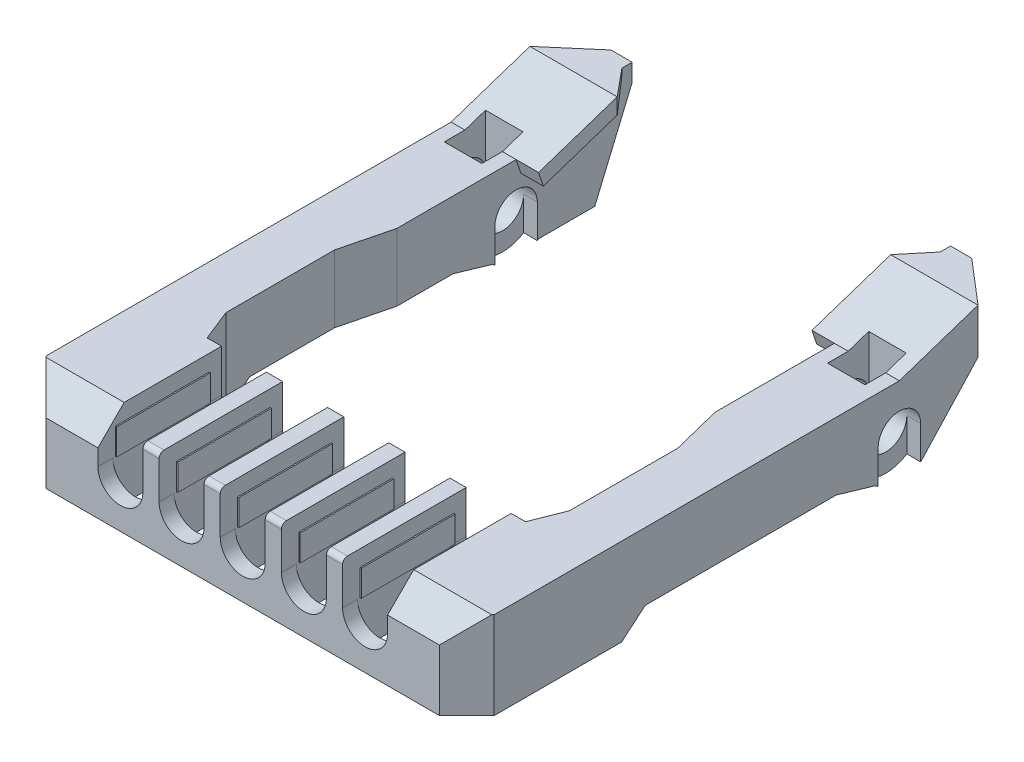
SolidWorks part; units mm, degrees
material "ABS"
ref_plane "Front Plane" through (0, 0, 0) normal (0, 0, 1) x (1, 0, 0)
ref_plane "Top Plane" through (0, 0, 0) normal (0, 1, 0) x (1, 0, 0)
ref_plane "Right Plane" through (0, 0, 0) normal (1, 0, 0) x (0, 0, -1)
sketch "Sketch1" plane through (0, 0, 0) normal (0, 1, 0) x (1, 0, 0)
  line L1 (-17.95, -4.95) -> (17.95, -4.95)
  line L2 (-17.95, -4.95) -> (-17.95, 4.95)
  line L3 (-17.95, 4.95) -> (17.95, 4.95)
  line L4 (17.95, -4.95) -> (17.95, 4.95)
  line L5 (-17.95, -4.95) -> (17.95, 4.95) construction
  line L6 (-17.95, 4.95) -> (17.95, -4.95) construction
  point P0 (0, 0)
extrude "Boss-Extrude1" add sketch "Sketch1" along normal blind 7 contours L2 L1 L4 L3
chamfer "Chamfer1" distance 2.192 angle 45 2 edges at (-17.95, 3.5, 4.95) (17.95, 3.5, 4.95)
sketch "Sketch2" plane through (0, 7, 0) normal (0, 1, 0) x (1, 0, 0)
  line L0 (-17.95, 4.95) -> (17.95, 4.95) construction
  line L1 (11.6, 4.95) -> (8, 4.95)
  line L2 (11.6, 4.95) -> (11.6, -4.95)
  line L3 (11.6, -4.95) -> (8, -4.95)
  line L4 (8, 4.95) -> (8, -4.95)
  line L5 (-15.758, -4.95) -> (15.758, -4.95) construction
  line L7 (6.7, 4.95) -> (6.7, -4.95)
  line L8 (6.7, 4.95) -> (3.1, 4.95)
  line L9 (3.1, 4.95) -> (3.1, -4.95)
  line L10 (6.7, -4.95) -> (3.1, -4.95)
  line L11 (1.8, 4.95) -> (1.8, -4.95)
  line L12 (1.8, 4.95) -> (-1.8, 4.95)
  line L13 (-1.8, 4.95) -> (-1.8, -4.95)
  line L14 (1.8, -4.95) -> (-1.8, -4.95)
  line L15 (-3.1, 4.95) -> (-3.1, -4.95)
  line L16 (-3.1, 4.95) -> (-6.7, 4.95)
  line L17 (-6.7, 4.95) -> (-6.7, -4.95)
  line L18 (-3.1, -4.95) -> (-6.7, -4.95)
  line L19 (-8, 4.95) -> (-8, -4.95)
  line L20 (-8, 4.95) -> (-11.6, 4.95)
  line L21 (-11.6, 4.95) -> (-11.6, -4.95)
  line L22 (-8, -4.95) -> (-11.6, -4.95)
  line L23 (17.95, -2.758) -> (17.95, 4.95) construction
  dimension "D2" = 3.6
  dimension "D3" = 5
  dimension "D4" = 3.6
  dimension "D5" = 1.3
  dimension "D6" = 3.6
  dimension "D7" = 1.3
  dimension "D8" = 3.6
  dimension "D9" = 1.3
  dimension "D10" = 3.6
  dimension "D11" = 1.3
  dimension "D12" = 16.15
extrude "Cut-Extrude1" cut sketch "Sketch2" against normal blind 3.4
chamfer "Chamfer2" distance 2.1 angle 45 2 edges at (13.679, 7, 4.95) (-13.679, 7, 4.95)
fillet "Fillet1" radius 0.4 4 edges at (7.35, 7, 4.95) (2.45, 7, 4.95) (-2.45, 7, 4.95) (-7.35, 7, 4.95)
sketch "Sketch3" plane through (0, 0, 4.95) normal (0, 0, 1) x (1, 0, 0)
  line L0 (17.95, 7) -> (17.95, 0) construction
  line L4 (-15.758, 0) -> (15.758, 0) construction
  circle A0 centre (9.8, 3.6) radius 1.8
  circle A1 centre (4.9, 3.6) radius 1.8
  circle A2 centre (0, 3.6) radius 1.8
  circle A3 centre (-4.9, 3.6) radius 1.8
  circle A4 centre (-9.8, 3.6) radius 1.8
  dimension "D1" = 3.6
  dimension "D2" = 3.6
  dimension "D6" = 4.9
  dimension "D7" = 4.9
  dimension "D3" = 5
  dimension "D4" = 4.9
  dimension "D5" = 4.9
  dimension "D8" = 17.95
extrude "Cut-Extrude2" cut sketch "Sketch3" against normal through all
sketch "Sketch4" plane through (-6.7, 0, 0) normal (1, 0, 0) x (0, 0, -1)
  line L0 (-2.758, 7) -> (4.95, 7) construction
  line L1 (3.95, 5.7) -> (-3.55, 5.7)
  line L2 (3.95, 5.7) -> (3.95, 3.6)
  line L3 (3.95, 3.6) -> (-3.55, 3.6)
  line L4 (-3.55, 5.7) -> (-3.55, 3.6)
  line L5 (-4.95, 0) -> (-4.95, 4.9) construction
  dimension "D1" = 1.3
  dimension "D2" = 7.5
  dimension "D3" = 3.4
  dimension "D4" = 1.4
extrude "Boss-Extrude2" add sketch "Sketch4" along normal blind 0.1 contours L2 L1 L4 L3
sketch "Sketch5" plane through (-1.8, 0, 0) normal (1, 0, 0) x (0, 0, -1)
  line L0 (3.95, 5.7) -> (-3.55, 5.7)
  line L1 (3.95, 5.7) -> (3.95, 3.6)
  line L2 (3.95, 3.6) -> (-3.55, 3.6)
  line L3 (-3.55, 5.7) -> (-3.55, 3.6)
  line L4 (-2.758, 7) -> (4.95, 7) construction
  line L5 (-4.95, 0) -> (-4.95, 4.9) construction
  dimension "D1" = 1.3
  dimension "D2" = 1.4
extrude "Boss-Extrude3" add sketch "Sketch5" along normal blind 0.1
sketch "Sketch6" plane through (3.1, 0, 0) normal (1, 0, 0) x (0, 0, -1)
  line L0 (3.95, 5.7) -> (-3.55, 5.7)
  line L1 (3.95, 5.7) -> (3.95, 3.6)
  line L2 (3.95, 3.6) -> (-3.55, 3.6)
  line L3 (-3.55, 5.7) -> (-3.55, 3.6)
  line L4 (-2.758, 7) -> (4.95, 7) construction
  line L5 (-4.95, 0) -> (-4.95, 4.9) construction
  dimension "D1" = 1.3
  dimension "D2" = 1.4
  dimension "D3" = 7.5
extrude "Boss-Extrude4" add sketch "Sketch6" along normal blind 0.1
sketch "Sketch7" plane through (8, 0, 0) normal (1, 0, 0) x (0, 0, -1)
  line L0 (3.95, 5.7) -> (-3.55, 5.7)
  line L1 (3.95, 5.7) -> (3.95, 3.6)
  line L2 (3.95, 3.6) -> (-3.55, 3.6)
  line L3 (-3.55, 5.7) -> (-3.55, 3.6)
  line L4 (-2.758, 7) -> (4.95, 7) construction
  line L5 (-4.95, 0) -> (-4.95, 4.9) construction
  dimension "D1" = 1.3
  dimension "D2" = 1.4
  dimension "D3" = 7.5
extrude "Boss-Extrude5" add sketch "Sketch7" along normal blind 0.1
sketch "Sketch8" plane through (-11.6, 0, 0) normal (1, 0, 0) x (0, 0, -1)
  line L0 (3.95, 5.7) -> (-3.55, 5.7)
  line L1 (3.95, 5.7) -> (3.95, 3.6)
  line L2 (3.95, 3.6) -> (-3.55, 3.6)
  line L3 (-3.55, 5.7) -> (-3.55, 3.6)
  line L4 (-2.758, 7) -> (4.95, 7) construction
  line L5 (-4.95, 0) -> (-4.95, 4.9) construction
  dimension "D1" = 1.3
  dimension "D2" = 1.4
extrude "Boss-Extrude6" add sketch "Sketch8" along normal blind 0.1
sketch "Sketch9" plane through (-8, 0, 0) normal (-1, 0, 0) x (0, 0, 1)
  line L0 (3.55, 5.7) -> (-3.95, 5.7)
  line L1 (3.55, 5.7) -> (3.55, 3.6)
  line L2 (3.55, 3.6) -> (-3.95, 3.6)
  line L3 (-3.95, 5.7) -> (-3.95, 3.6)
  line L4 (2.758, 7) -> (-4.95, 7) construction
  line L5 (4.95, 4.9) -> (4.95, 0) construction
  dimension "D1" = 1.3
  dimension "D2" = 1.4
  dimension "D3" = 7.5
extrude "Boss-Extrude7" add sketch "Sketch9" along normal blind 0.1
sketch "Sketch10" plane through (-3.1, 0, 0) normal (-1, 0, 0) x (0, 0, 1)
  line L0 (3.55, 5.7) -> (-3.95, 5.7)
  line L1 (3.55, 5.7) -> (3.55, 3.6)
  line L2 (3.55, 3.6) -> (-3.95, 3.6)
  line L3 (-3.95, 5.7) -> (-3.95, 3.6)
  line L4 (2.758, 7) -> (-4.95, 7) construction
  line L5 (4.95, 4.9) -> (4.95, 0) construction
  dimension "D1" = 1.3
  dimension "D2" = 1.4
  dimension "D3" = 7.5
extrude "Boss-Extrude8" add sketch "Sketch10" along normal blind 0.1
sketch "Sketch11" plane through (1.8, 0, 0) normal (-1, 0, 0) x (0, 0, 1)
  line L0 (3.55, 5.7) -> (-3.95, 5.7)
  line L1 (3.55, 5.7) -> (3.55, 3.6)
  line L2 (3.55, 3.6) -> (-3.95, 3.6)
  line L3 (-3.95, 5.7) -> (-3.95, 3.6)
  line L4 (2.758, 7) -> (-4.95, 7) construction
  line L5 (4.95, 4.9) -> (4.95, 0) construction
  dimension "D1" = 1.3
  dimension "D2" = 1.4
  dimension "D3" = 7.5
extrude "Boss-Extrude9" add sketch "Sketch11" along normal blind 0.1
sketch "Sketch12" plane through (6.7, 0, 0) normal (-1, 0, 0) x (0, 0, 1)
  line L0 (3.55, 5.7) -> (-3.95, 5.7)
  line L1 (3.55, 5.7) -> (3.55, 3.6)
  line L2 (3.55, 3.6) -> (-3.95, 3.6)
  line L3 (-3.95, 5.7) -> (-3.95, 3.6)
  line L4 (2.758, 7) -> (-4.95, 7) construction
  line L5 (4.95, 4.9) -> (4.95, 0) construction
  dimension "D1" = 1.3
  dimension "D2" = 1.4
  dimension "D3" = 7.5
extrude "Boss-Extrude10" add sketch "Sketch12" along normal blind 0.1
sketch "Sketch13" plane through (11.6, 0, 0) normal (-1, 0, 0) x (0, 0, 1)
  line L0 (3.55, 5.7) -> (-3.95, 5.7)
  line L1 (3.55, 5.7) -> (3.55, 3.6)
  line L2 (3.55, 3.6) -> (-3.95, 3.6)
  line L3 (-3.95, 5.7) -> (-3.95, 3.6)
  line L4 (2.758, 7) -> (-4.95, 7) construction
  line L5 (4.95, 4.9) -> (4.95, 0) construction
  dimension "D1" = 7.5
  dimension "D2" = 1.3
  dimension "D3" = 1.4
extrude "Boss-Extrude11" add sketch "Sketch13" along normal blind 0.1
sketch "Sketch14" plane through (0, 0, -4.95) normal (0, 0, -1) x (-1, 0, 0)
  line L5 (17.95, 0) -> (-17.95, 0) construction
  line L6 (17.95, 7) -> (12.75, 7)
  line L7 (17.95, 7) -> (17.95, 0)
  line L8 (17.95, 0) -> (12.75, 0)
  line L9 (12.75, 7) -> (12.75, 0)
  dimension "D1" = 5.2
extrude "Boss-Extrude13" add sketch "Sketch14" along normal blind 2.5
sketch "Sketch16" plane through (0, 7, 0) normal (0, 1, 0) x (1, 0, 0)
  line L0 (-12.75, 7.45) -> (-13.75, 7.45)
  line L1 (-17.95, 7.45) -> (-12.75, 7.45) construction
  line L2 (-12.75, 7.45) -> (-12.75, 4.95) construction
  line L3 (-13.75, 7.45) -> (-12.75, 4.95)
  line L4 (-12.75, 4.95) -> (-12.75, 7.45)
extrude "Cut-Extrude4" cut sketch "Sketch16" against normal through all
sketch "Sketch17" plane through (0, 0, -7.45) normal (0, 0, -1) x (-1, 0, 0)
  line L0 (13.75, 0) -> (13.75, 7) construction
  line L1 (17.95, 7) -> (13.75, 7)
  line L2 (17.95, 7) -> (17.95, 0)
  line L3 (17.95, 0) -> (13.75, 0)
  line L4 (13.75, 7) -> (13.75, 0)
extrude "Boss-Extrude15" add sketch "Sketch17" along normal blind 1.9
sketch "Sketch19" plane through (-13.75, 0, 0) normal (1, 0, 0) x (0, 0, -1)
  line L1 (9.35, 7) -> (9.35, 0) construction
  line L2 (9.35, 1.6) -> (7.45, 0)
  line L3 (7.45, 0) -> (9.35, 0)
  line L4 (9.35, 0) -> (9.35, 1.6)
extrude "Cut-Extrude5" cut sketch "Sketch19" against normal through all contours L2 L3 L4
sketch "Sketch20" plane through (0, 0, -9.35) normal (0, 0, -1) x (-1, 0, 0)
  line L1 (13.75, 7) -> (17.95, 7)
  line L2 (13.75, 7) -> (13.75, 1.6)
  line L3 (13.75, 1.6) -> (17.95, 1.6)
  line L4 (17.95, 7) -> (17.95, 1.6)
extrude "Boss-Extrude16" add sketch "Sketch20" along normal blind 6.8
sketch "Sketch21" plane through (0, 0, -16.15) normal (0, 0, -1) x (-1, 0, 0)
  line L1 (12.75, 7) -> (17.95, 7)
  line L2 (12.75, 7) -> (12.75, 1.6)
  line L3 (12.75, 1.6) -> (17.95, 1.6)
  line L4 (17.95, 7) -> (17.95, 1.6)
extrude "Boss-Extrude17" add sketch "Sketch21" along normal blind 4
sketch "Sketch22" plane through (0, 7, 0) normal (0, 1, 0) x (1, 0, 0)
  line L0 (-12.75, 20.15) -> (-13.75, 16.15)
  line L1 (-13.75, 16.15) -> (-12.75, 16.15)
  line L2 (-12.75, 16.15) -> (-12.75, 20.15)
extrude "Cut-Extrude6" cut sketch "Sketch22" against normal through all
sketch "Sketch23" plane through (0, 0, -20.15) normal (0, 0, -1) x (-1, 0, 0)
  line L1 (17.95, 7) -> (12.75, 7)
  line L2 (17.95, 7) -> (17.95, 1.6)
  line L3 (17.95, 1.6) -> (12.75, 1.6)
  line L4 (12.75, 7) -> (12.75, 1.6)
extrude "Boss-Extrude18" add sketch "Sketch23" along normal blind 4.5
sketch "Sketch25" plane through (0, 0, -24.65) normal (0, 0, -1) x (-1, 0, 0)
  line L0 (12.75, 7) -> (12.75, 0) construction
  line L1 (17.95, 7) -> (12.75, 7)
  line L2 (17.95, 7) -> (17.95, 0.6)
  line L3 (17.95, 0.6) -> (12.75, 0.6)
  line L4 (12.75, 7) -> (12.75, 0.6)
  dimension "D1" = 6.4
extrude "Boss-Extrude19" add sketch "Sketch25" along normal blind 3.4
sketch "Sketch26" plane through (-12.75, 0, 0) normal (1, 0, 0) x (0, 0, -1)
  line L0 (24.65, 1.6) -> (28.05, 0.6)
  line L1 (28.05, 0.6) -> (24.65, 0.6)
  line L2 (24.65, 0.6) -> (24.65, 1.6)
extrude "Cut-Extrude7" cut sketch "Sketch26" against normal through all
sketch "Sketch27" plane through (0, 0, -28.05) normal (0, 0, -1) x (-1, 0, 0)
  line L0 (12.75, 0.6) -> (17.95, 0.6) construction
  line L1 (17.95, 7) -> (12.75, 7)
  line L2 (17.95, 7) -> (17.95, 0.6)
  line L3 (17.95, 0.6) -> (12.75, 0.6)
  line L4 (12.75, 7) -> (12.75, 0.6)
  line L5 (12.75, 7) -> (12.75, 0.6) construction
extrude "Boss-Extrude20" add sketch "Sketch27" along normal blind 1.65
sketch "Sketch28" plane through (0, 0, -29.7) normal (0, 0, -1) x (-1, 0, 0)
  line L0 (12.75, 7) -> (12.75, 0) construction
  line L1 (17.95, 0.6) -> (12.75, 0.6)
  line L2 (17.95, 0.6) -> (17.95, 9.1)
  line L3 (17.95, 9.1) -> (12.75, 9.1)
  line L4 (12.75, 0.6) -> (12.75, 9.1)
  dimension "D1" = 8.5
extrude "Boss-Extrude21" add sketch "Sketch28" along normal blind 9.3
sketch "Sketch29" plane through (-12.75, 0, 0) normal (1, 0, 0) x (0, 0, -1)
  line L1 (39, 9.1) -> (29.7, 9.1) construction
  line L2 (36, 9.1) -> (29.7, 7)
  line L5 (36, 9.1) -> (29.7, 9.1)
  line L6 (29.7, 9.1) -> (29.7, 7)
extrude "Cut-Extrude8" cut sketch "Sketch29" against normal through all contours L5 L6 L2
sketch "Sketch30" plane through (-12.75, 0, 0) normal (1, 0, 0) x (0, 0, -1)
  line L0 (-2.758, 0) -> (41.3821, 0)
  circle A0 centre (29.7, 3.2) radius 3.17
extrude "Boss-Extrude22" add sketch "Sketch30" against normal through all contours A0
sketch "Sketch31" plane through (-12.75, 0, 0) normal (1, 0, 0) x (0, 0, -1)
  line L0 (29.7, 0.03) -> (29.7, 3.2)
  arc A0 (27.7761, 0.6805) -> (31.5135, 0.6) centre (29.7, 3.2) ccw construction
  circle A1 centre (29.7, 3.2) radius 1.7
extrude "Cut-Extrude9" cut sketch "Sketch31" against normal through all contours A1
sketch "Sketch32" plane through (-12.75, 0, 0) normal (1, 0, 0) x (0, 0, -1)
  line L0 (29.7, 3.2) -> (28, 3.2)
  line L1 (28, 3.2) -> (28, 0.5244)
  line L2 (29.7, 3.2) -> (31.4, 3.2)
  line L3 (31.4, 3.2) -> (31.4, 0.5244)
  line L4 (28, 0.5244) -> (28, -0.1208)
  line L5 (28, -0.1208) -> (31.4, -0.1208)
  line L6 (31.4, -0.1208) -> (31.4, 0.5244)
  circle A0 centre (29.7, 3.2) radius 1.7 construction
  arc A1 (27.7761, 0.6805) -> (31.5135, 0.6) centre (29.7, 3.2) ccw construction
extrude "Cut-Extrude10" cut sketch "Sketch32" against normal blind 1.1 contours L6 L3 L2 L0 L1 L4 L5
sketch "Sketch33" plane through (-17.95, 0, 0) normal (-1, 0, 0) x (0, 0, 1)
  line L0 (-31.4, 3.2) -> (-31.4, -0.6408)
  line L1 (-31.4, -0.6408) -> (-28, -0.6408)
  line L2 (-28, -0.6408) -> (-28, 3.2)
  line L3 (-28, 3.2) -> (-31.4, 3.2)
  circle A0 centre (-29.7, 3.2) radius 1.7 construction
extrude "Cut-Extrude11" cut sketch "Sketch33" against normal blind 1.1
sketch "Sketch34" plane through (-12.75, 0, 0) normal (1, 0, 0) x (0, 0, -1)
  line L3 (29.7, 7) -> (30.0795, 5.8616)
  line L4 (36.3795, 7.9616) -> (30.0795, 5.8616)
  line L5 (36, 7.8351) -> (30.0795, 5.8616)
  line L6 (36, 9.1) -> (36, 7.8351)
  line L7 (36, 9.1) -> (29.7, 7)
  dimension "D1" = 1.2
extrude "Boss-Extrude23" add sketch "Sketch34" along normal blind 1.8
sketch "Sketch35" plane through (-12.75, 0, 0) normal (1, 0, 0) x (0, 0, -1)
  line L0 (36, 7.8351) -> (38.1721, 8.5591)
  line L1 (38.1721, 8.5591) -> (38.1721, 9.1)
  line L2 (39, 9.1) -> (36, 9.1) construction
  line L3 (38.1721, 9.1) -> (36, 9.1)
  line L4 (36, 9.1) -> (36, 7.8351)
extrude "Boss-Extrude24" add sketch "Sketch35" along normal blind 1.8
sketch "Sketch36" plane through (0, 9.1, 0) normal (0, 1, 0) x (1, 0, 0)
  line L0 (-10.95, 36) -> (-12.75, 38.1721)
  line L1 (-12.75, 38.1721) -> (-10.95, 38.1721)
  line L2 (-10.95, 38.1721) -> (-10.95, 36)
extrude "Cut-Extrude12" cut sketch "Sketch36" against normal through all
sketch "Sketch37" plane through (-12.75, 0, 0) normal (1, 0, 0) x (0, 0, -1)
  line L1 (39, 9.1) -> (39, 0.6) construction
  line L2 (39, 7.7) -> (36, 0.6)
  line L3 (39, 0.6) -> (31.5135, 0.6) construction
  line L4 (36, 0.6) -> (39, 0.6)
  line L5 (39, 0.6) -> (39, 7.7)
extrude "Cut-Extrude13" cut sketch "Sketch37" against normal through all
sketch "Sketch38" plane through (0, 0, 0) normal (0, -1, 0) x (1, 0, 0)
  line L7 (17.95, 2.758) -> (17.95, -4.95) construction
  line L8 (8, 3.75) -> (11.6, 3.75)
  line L9 (8, 3.75) -> (8, -3.75)
  line L10 (8, -3.75) -> (11.6, -3.75)
  line L11 (11.6, 3.75) -> (11.6, -3.75)
  line L12 (-15.758, 4.95) -> (15.758, 4.95) construction
  line L13 (-12.75, -4.95) -> (17.95, -4.95) construction
  line L15 (3.1, 3.75) -> (3.1, -3.75)
  line L16 (3.1, 3.75) -> (6.7, 3.75)
  line L17 (6.7, 3.75) -> (6.7, -3.75)
  line L18 (3.1, -3.75) -> (6.7, -3.75)
  line L19 (-1.8, 3.75) -> (-1.8, -3.75)
  line L20 (-1.8, 3.75) -> (1.8, 3.75)
  line L21 (1.8, 3.75) -> (1.8, -3.75)
  line L22 (-1.8, -3.75) -> (1.8, -3.75)
  line L23 (-6.7, 3.75) -> (-6.7, -3.75)
  line L24 (-6.7, 3.75) -> (-3.1, 3.75)
  line L25 (-3.1, 3.75) -> (-3.1, -3.75)
  line L26 (-6.7, -3.75) -> (-3.1, -3.75)
  line L27 (-11.6, 3.75) -> (-11.6, -3.75)
  line L28 (-11.6, 3.75) -> (-8, 3.75)
  line L29 (-8, 3.75) -> (-8, -3.75)
  line L30 (-11.6, -3.75) -> (-8, -3.75)
  dimension "D1" = 3.6
  dimension "D2" = 6.35
  dimension "D3" = 1.2
  dimension "D4" = 1.2
  dimension "D5" = 5
extrude "Cut-Extrude14" cut sketch "Sketch38" against normal blind 3.6
sketch "Sketch39" plane through (0, 9.1, 0) normal (0, 1, 0) x (1, 0, 0)
  line L1 (-17.95, 39) -> (-12.75, 39) construction
  line L2 (-14.45, 39) -> (-17.95, 36)
  line L3 (-17.95, 36) -> (-17.95, 39)
  line L4 (-17.95, 39) -> (-14.45, 39)
extrude "Cut-Extrude15" cut sketch "Sketch39" against normal through all contours L2 L3 L4
sketch "Sketch43" plane through (0, 0.6, 0) normal (0, -1, 0) x (1, 0, 0)
  line L3 (-13.95, -32.5) -> (-13.95, -39)
  line L4 (-14.45, -39) -> (-12.75, -39) construction
  line L7 (-16.75, -32.5) -> (-13.95, -32.5)
  line L8 (-16.75, -32.5) -> (-16.75, -39)
  line L9 (-16.75, -39) -> (-13.95, -39)
extrude "Cut-Extrude16" cut sketch "Sketch43" against normal blind 6 contours L3 L9 L8 L7
sketch "Sketch44" plane through (-17.95, 0, 0) normal (-1, 0, 0) x (0, 0, 1)
  line L1 (-37.0286, 6.6) -> (-31.4572, 0.5616)
  line L2 (-31.4572, 0.5616) -> (-36.7157, 0.5616)
  line L3 (-36.7157, 0.5616) -> (-37.0286, 6.6)
  arc A0 (-31.5135, 0.6) -> (-31.4, 0.5244) centre (-29.7, 3.2) ccw construction
extrude "Cut-Extrude17" cut sketch "Sketch44" against normal blind 3 contours L1 L2 L3
sketch "Sketch45" plane through (0, -15.4195, -16.7121) normal (0, -0.6781, -0.735) x (-1, 0, 0)
  line L0 (13.95, 26.8894) -> (13.95, 30.982) construction
  line L1 (17.95, 21.7443) -> (13.95, 21.7443)
  line L2 (17.95, 21.7443) -> (17.95, 29.9606)
  line L3 (17.95, 29.9606) -> (13.95, 29.9606)
  line L4 (13.95, 21.7443) -> (13.95, 29.9606)
extrude "Cut-Extrude19" cut sketch "Sketch45" along normal through all
sketch "Sketch47" plane through (0, 7, 0) normal (0, 1, 0) x (1, 0, 0)
  line L0 (-17.95, 29.7) -> (-12.75, 29.7) construction
  line L2 (-16.85, 29.7) -> (-16.85, 28.05)
  line L3 (-16.85, 28.05) -> (-13.85, 28.05)
  line L4 (-13.85, 29.7) -> (-13.85, 28.05)
  line L5 (-12.75, 29.7) -> (-12.75, 20.15) construction
  line L6 (-17.95, -2.758) -> (-17.95, 29.7) construction
  line L9 (-16.85, 29.7) -> (-16.85, 31.35)
  line L10 (-16.85, 31.35) -> (-13.85, 31.35)
  line L11 (-13.85, 29.7) -> (-13.85, 31.35)
  dimension "D1" = 1.1
  dimension "D2" = 1.1
extrude "Cut-Extrude20" cut sketch "Sketch47" against normal blind 3.85 and the other way through all contours L2 L3 L4 L11 L10 L9
ref_plane "Plane12" through (0, 0, 0) normal (1, 0, 0) x (0, 0, -1)
mirror "Mirror1" about plane through (0, 0, 0) normal (1, 0, 0) of bodies 145
sketch "Sketch49" plane through (0, 0, 0) normal (0, -1, 0) x (1, 0, 0)
  line L2 (-14.95, -9.35) -> (-14.95, -7.45)
  line L3 (-14.95, -9.35) -> (-14.95, -7.45)
  line L4 (-14.8642, -7.0043) -> (-14.95, -7.2189)
  line L5 (-14.8642, -7.0043) -> (-13.8642, -4.5043)
  line L6 (-14.8642, -7.0043) -> (-13.8642, -4.5043)
  line L7 (-14.95, -7.45) -> (-14.95, -7.2189)
  line L8 (-13.95, -24.65) -> (-16.75, -24.65)
  line L11 (-12.8, 3.75) -> (-12.8, -3.75)
  line L12 (-12.8, 3.75) -> (-12.8, -3.75)
  line L13 (-13.8642, -4.5043) -> (-13.5768, -3.75)
  line L14 (-15.758, 3.75) -> (15.758, 3.75)
  line L15 (-15.2609, 3.75) -> (-12.8, 3.75)
  line L16 (-13.5768, -3.75) -> (-12.8, -3.75)
  line L22 (-14.9094, 4.1015) -> (-17.1015, 1.9094)
  line L23 (-15.2609, 3.75) -> (-16.75, 2.2609)
  line L25 (-16.75, 2.758) -> (-16.75, -7.45)
  line L26 (-16.75, 2.2609) -> (-16.75, -7.45)
  line L28 (-16.75, -9.35) -> (-16.75, -7.45)
  line L29 (-16.75, -9.35) -> (-16.75, -7.45)
  line L31 (-16.75, -24.65) -> (-16.75, -9.35)
  line L32 (-16.75, -24.65) -> (-16.75, -9.35)
  line L41 (-14.95, -16.2977) -> (-14.95, -9.35)
  line L42 (-13.95, -20.2977) -> (-14.95, -16.2977)
  line L43 (-13.95, -24.65) -> (-13.95, -20.2977)
  line L44 (-14.95, -16.2977) -> (-14.95, -9.35)
  line L45 (-13.95, -20.2977) -> (-14.95, -16.2977)
  line L46 (-13.95, -24.65) -> (-13.95, -20.2977)
  dimension "D1" = 1.2
  dimension "D2" = 1.2
  dimension "D3" = 1.2
  dimension "D4" = 1.2
  dimension "D5" = 1.2
  dimension "D6" = 1.2
  dimension "D7" = 1.2
  dimension "D8" = 1.2
  dimension "D9" = 1.2
extrude "Cut-Extrude21" cut sketch "Sketch49" against normal blind 5.9
mirror "Mirror2" about plane through (0, 0, 0) normal (1, 0, 0) of "Cut-Extrude21"
